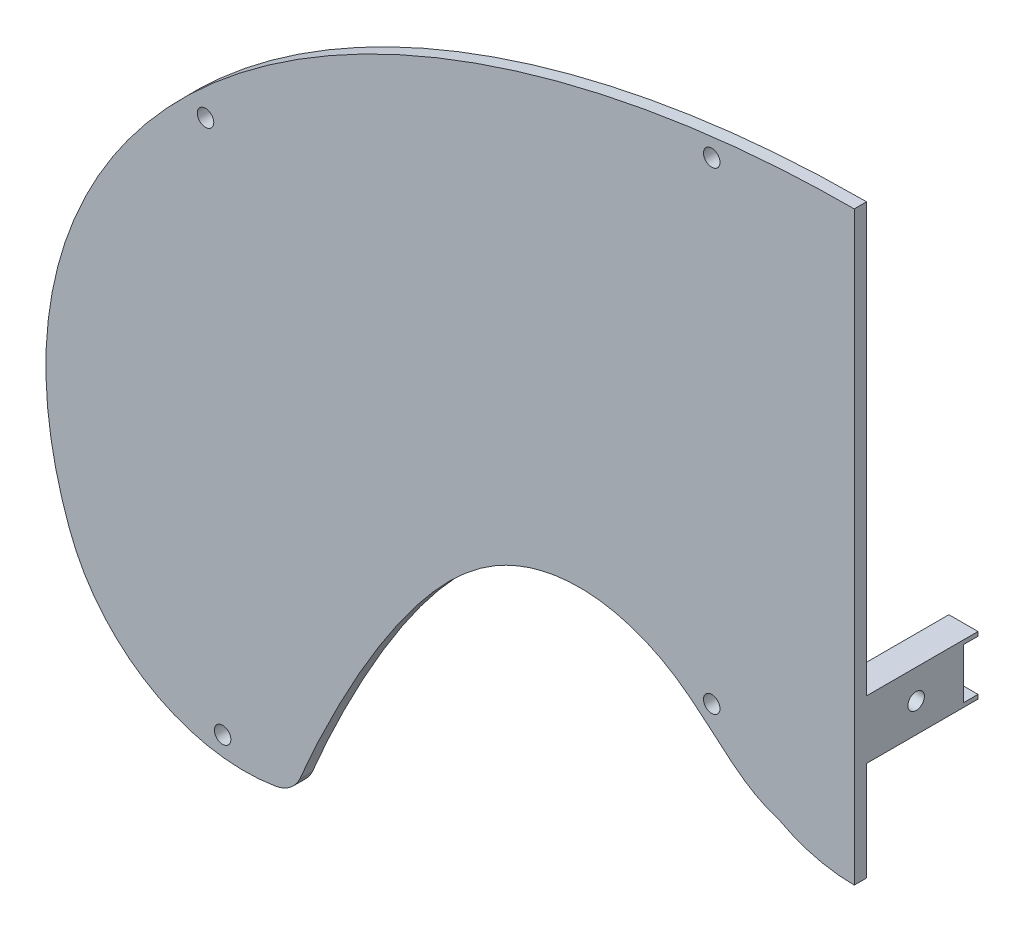
SolidWorks part; units mm, degrees
ref_plane "Alzado" through (0, 0, 0) normal (0, 0, 1) x (1, 0, 0)
ref_plane "Planta" through (0, 0, 0) normal (0, 1, 0) x (1, 0, 0)
ref_plane "Vista lateral" through (0, 0, 0) normal (1, 0, 0) x (0, 0, -1)
sketch "Croquis7" plane through (0, 0, 0) normal (0, 0, 1) x (-1, 0, 0)
  circle A31 centre (-153.1105, 56.1657) radius 2.25
  circle A33 centre (-34.5152, -9.6156) radius 2.25
  circle A35 centre (34.5978, -9.6156) radius 2
  arc A41 (140.3481, 60.5359) -> (134.4676, 56.1109) centre (141.679, 52.6474) ccw
  arc A42 (18.5035, 6.4502) -> (0.0413, 11.1657) centre (0.0413, -27.3343) ccw
  arc A43 (0.0413, 11.1657) -> (-18.4209, 6.4502) centre (0.0413, -27.3343) ccw
  arc A44 (190.316, 31.4795) -> (140.3481, 60.5359) centre (147.8664, 15.9723) ccw
  arc A45 (-134.385, 56.1109) -> (-140.2655, 60.5359) centre (-141.5964, 52.6474) ccw
  circle A47 centre (153.1931, 56.1657) radius 2
  circle A49 centre (-157.2515, -72.2296) radius 2.25
  circle A51 centre (-34.5152, -124.3045) radius 2.25
  circle A53 centre (34.5978, -124.3045) radius 2
  circle A55 centre (157.3341, -71.3124) radius 2
  spline S34 degree 3 poles (134.4676, 56.1109) (134.1497, 55.3341) (133.823, 54.562) (133.1625, 53.0214) (132.8278, 52.2534) (131.8131, 49.9551) (129.7405, 45.3812) (127.5541, 40.867) (124.537, 34.9015) (122.9771, 31.9456) (119.7406, 26.0953) (118.0639, 23.2008) (115.4414, 18.9154) (114.5493, 17.4963) (112.7238, 14.6799) (111.7904, 13.2827) (108.9309, 9.1433) (106.9422, 6.4488) (103.7895, 2.5408) (102.71, 1.2608) (101.0385, -0.6181) (100.4726, -1.2376) (99.3214, -2.461) (98.7352, -3.0657) (96.9496, -4.8484) (95.7253, -5.9925) (93.1935, -8.1717) (91.8856, -9.2063) (89.1637, -11.1369) (87.7504, -12.0335) (85.5424, -13.2632) (84.7899, -13.6545) (83.2733, -14.3869) (82.5072, -14.7293) (80.1852, -15.6842) (78.6055, -16.2244) (76.1869, -16.8847) (75.3725, -17.0799) (73.7268, -17.4186) (72.8936, -17.5624) (68.7052, -18.1459) (65.3663, -18.1723) (61.2066, -17.6857) (60.3753, -17.5622) (58.7142, -17.2624) (57.8851, -17.086) (55.4328, -16.486) (53.8333, -15.9902) (50.7014, -14.8176) (49.1688, -14.1408) (46.9194, -12.9918) (46.1761, -12.5854) (44.7184, -11.7347) (44.0033, -11.2901) (41.8979, -9.9002) (40.5487, -8.8972) (37.9154, -6.8) (36.6314, -5.7052) (34.0802, -3.4945) (32.813, -2.378) (30.2367, -0.2008) (28.9278, 0.8604) (26.2007, 2.837) (24.7825, 3.7527) (22.5133, 4.9374) (21.7312, 5.3009) (20.5388, 5.7796) (20.1373, 5.9286) (19.5289, 6.1355) (19.3251, 6.2018) (18.9151, 6.3283) (18.7092, 6.3889) (18.5035, 6.4502) knots 0 0 0 0 0.015625 0.015625 0.03125 0.03125 0.0625 0.125 0.125 0.1875 0.1875 0.25 0.25 0.28125 0.28125 0.3125 0.3125 0.375 0.375 0.40625 0.40625 0.421875 0.421875 0.4375 0.4375 0.46875 0.46875 0.5 0.5 0.53125 0.53125 0.546875 0.546875 0.5625 0.5625 0.59375 0.59375 0.609375 0.609375 0.625 0.625 0.6875 0.6875 0.703125 0.703125 0.71875 0.71875 0.75 0.75 0.78125 0.78125 0.796875 0.796875 0.8125 0.8125 0.84375 0.84375 0.875 0.875 0.90625 0.90625 0.9375 0.9375 0.96875 0.96875 0.984375 0.984375 0.992188 0.992188 0.996094 0.996094 1 1 1 1
  spline S35 degree 3 poles (0.0413, -130.8343) (6.1345, -130.8343) (18.2614, -130.4542) (30.2709, -129.3262) (42.2211, -127.8206) (48.1667, -126.8792) (59.9963, -124.6051) (65.8805, -123.2725) (74.6576, -120.9611) (79.034, -119.7273) (83.391, -118.3705) (86.2913, -117.4379) (87.7403, -116.9573) (94.9485, -114.4913) (100.6127, -112.3132) (111.7238, -107.5208) (117.1707, -104.9068) (127.8256, -99.1992) (133.0339, -96.1063) (139.3732, -91.8969) (140.6325, -91.0378) (143.1331, -89.2836) (144.3749, -88.388) (148.0522, -85.6602) (150.4464, -83.7821) (157.4477, -77.9604) (161.8749, -73.8302) (168.1008, -67.2053) (170.1073, -64.9256) (173.0021, -61.3872) (173.9479, -60.1879) (175.7992, -57.7476) (176.704, -56.5073) (181.0878, -50.2489) (184.1754, -45.0224) (188.0971, -36.8106) (189.2858, -34.0112) (190.6103, -30.4274) (190.8671, -29.7064) (191.3642, -28.2557) (191.6048, -27.5249) (192.2983, -25.3286) (192.7227, -23.8598) (194.6557, -16.493) (195.5989, -10.5266) (196.0792, -1.4638) (196.0831, 1.576) (195.8454, 6.1652) (195.725, 7.7032) (195.4053, 10.7544) (195.2061, 12.2713) (194.0174, 19.8128) (192.4537, 25.7099) (190.316, 31.4795) knots 0 0 0 0 0.0625 0.125 0.125 0.1875 0.1875 0.25 0.25 0.28125 0.296875 0.296875 0.3125 0.3125 0.375 0.375 0.4375 0.4375 0.5 0.5 0.515625 0.515625 0.53125 0.53125 0.5625 0.5625 0.625 0.625 0.65625 0.65625 0.671875 0.671875 0.6875 0.6875 0.75 0.75 0.78125 0.78125 0.789062 0.789062 0.796875 0.796875 0.8125 0.8125 0.875 0.875 0.90625 0.90625 0.921875 0.921875 0.9375 0.9375 1 1 1 1
  spline S36 degree 3 poles (-190.2396, 31.4627) (-192.3753, 25.6964) (-193.931, 19.8179) (-195.353, 10.8241) (-195.6746, 7.7968) (-195.9176, 3.2095) (-195.9586, 1.6681) (-195.9588, -1.3991) (-195.9184, -2.9265) (-195.5185, -10.5339) (-194.5674, -16.5243) (-192.6293, -23.8987) (-192.204, -25.3678) (-191.5098, -27.5631) (-191.2689, -28.2939) (-190.7708, -29.7454) (-190.5134, -30.4669) (-189.1858, -34.0543) (-187.9935, -36.8588) (-185.3684, -42.3469) (-183.9355, -45.0306) (-181.6166, -48.9709) (-180.8153, -50.2701) (-179.1576, -52.8408) (-178.2995, -54.1146) (-173.8945, -60.3876) (-170.029, -65.0712) (-161.7345, -73.886) (-157.3041, -78.0158) (-151.4553, -82.8734) (-150.2699, -83.8296) (-147.8686, -85.7121) (-146.6511, -86.6395) (-142.9656, -89.3694) (-140.4706, -91.1152) (-132.8814, -96.1488) (-127.6832, -99.2332) (-117.0444, -104.9282) (-111.6035, -107.5381) (-100.5002, -112.325) (-94.8377, -114.5017) (-87.6288, -116.9669) (-86.1801, -117.4472) (-83.2812, -118.3789) (-78.9261, -119.7345) (-74.5518, -120.9675) (-65.7783, -123.2771) (-59.8964, -124.6087) (-48.0711, -126.8813) (-42.1276, -127.8222) (-30.181, -129.3269) (-18.1749, -130.4544) (-6.0508, -130.8343) (0.0413, -130.8343) knots 0 0 0 0 0.0625 0.0625 0.09375 0.09375 0.109375 0.109375 0.125 0.125 0.1875 0.1875 0.203125 0.203125 0.210937 0.210937 0.21875 0.21875 0.25 0.25 0.28125 0.28125 0.296875 0.296875 0.3125 0.3125 0.375 0.375 0.4375 0.4375 0.453125 0.453125 0.46875 0.46875 0.5 0.5 0.5625 0.5625 0.625 0.625 0.6875 0.6875 0.703125 0.703125 0.71875 0.75 0.75 0.8125 0.8125 0.875 0.875 0.9375 1 1 1 1
  spline S37 degree 3 poles (-140.2655, 60.5359) (-142.8693, 60.9752) (-145.4727, 61.1815) (-149.3774, 61.1563) (-150.6788, 61.0918) (-152.6309, 60.9098) (-153.2815, 60.8349) (-154.5828, 60.6562) (-155.2349, 60.5521) (-158.4768, 59.9615) (-160.9933, 59.2705) (-164.6567, 57.918) (-165.8592, 57.4143) (-167.6345, 56.578) (-168.2215, 56.2858) (-169.3859, 55.674) (-169.9645, 55.3537) (-172.8074, 53.6975) (-174.9374, 52.1926) (-177.9226, 49.6738) (-178.8825, 48.7905) (-180.2687, 47.3985) (-180.7218, 46.9233) (-181.6098, 45.9503) (-182.0445, 45.4525) (-184.1498, 42.9327) (-185.6364, 40.7989) (-188.2287, 36.3043) (-189.3345, 33.9434) (-190.2396, 31.4627) knots 0 0 0 0 0.125 0.125 0.1875 0.1875 0.21875 0.21875 0.25 0.25 0.375 0.375 0.4375 0.4375 0.46875 0.46875 0.5 0.5 0.625 0.625 0.6875 0.6875 0.71875 0.71875 0.75 0.75 0.875 0.875 1 1 1 1
  spline S38 degree 3 poles (-18.4209, 6.4502) (-18.6239, 6.3897) (-18.8274, 6.3298) (-19.2315, 6.2052) (-19.4321, 6.1401) (-20.0298, 5.9374) (-20.4228, 5.7921) (-21.5864, 5.3276) (-23.8516, 4.2837) (-25.9572, 2.9439) (-27.9958, 1.4801) (-28.6649, 0.971) (-29.9839, -0.0733) (-31.9328, -1.678) (-33.8306, -3.3482) (-37.6482, -6.6606) (-40.2236, -8.8297) (-43.7321, -11.1693) (-44.4478, -11.6193) (-45.9083, -12.4816) (-46.6541, -12.8941) (-48.91, -14.0595) (-50.4472, -14.7456) (-53.5879, -15.9362) (-55.1916, -16.4402) (-57.65, -17.0517) (-58.4788, -17.2315) (-60.153, -17.5399) (-60.9902, -17.6671) (-65.1772, -18.1706) (-68.5295, -18.1508) (-72.7235, -17.5765) (-73.5654, -17.4332) (-75.2277, -17.0942) (-76.0496, -16.8986) (-78.4886, -16.2359) (-80.0788, -15.693) (-82.4131, -14.7345) (-83.1827, -14.391) (-84.705, -13.6564) (-85.4593, -13.2643) (-87.6863, -12.0236) (-89.1091, -11.119) (-91.846, -9.1738) (-93.1593, -8.1323) (-95.6997, -5.9411) (-96.9266, -4.7914) (-99.3113, -2.4055) (-100.4707, -1.1677) (-102.7053, 1.3503) (-103.7843, 2.6341) (-106.932, 6.544) (-108.9096, 9.2293) (-112.6931, 14.7116) (-114.4983, 17.5091) (-117.9753, 23.1911) (-119.6467, 26.0756) (-122.8791, 31.9168) (-124.4399, 34.8734) (-127.4635, 40.8505) (-128.9258, 43.8693) (-131.0393, 48.4296) (-132.0766, 50.7187) (-133.0806, 53.0229) (-133.7409, 54.5632) (-134.0674, 55.335) (-134.385, 56.1109) knots 0 0 0 0 0.003906 0.003906 0.007812 0.007812 0.015625 0.015625 0.03125 0.0625 0.0625 0.078125 0.078125 0.09375 0.125 0.125 0.1875 0.1875 0.203125 0.203125 0.21875 0.21875 0.25 0.25 0.28125 0.28125 0.296875 0.296875 0.3125 0.3125 0.375 0.375 0.390625 0.390625 0.40625 0.40625 0.4375 0.4375 0.453125 0.453125 0.46875 0.46875 0.5 0.5 0.53125 0.53125 0.5625 0.5625 0.59375 0.59375 0.625 0.625 0.6875 0.6875 0.75 0.75 0.8125 0.8125 0.875 0.875 0.9375 0.9375 0.96875 0.984375 0.984375 1 1 1 1
extrude "Saliente-Extruir5" add sketch "Croquis7" along normal blind 3
sketch "Croquis8" plane through (0, 0, 3) normal (0, 0, 1) x (1, 0, 0)
  line L0 (0, 0) -> (0, 20) construction
  line L2 (-7.1, 27.1) -> (7.1, 27.1)
  line L3 (-7.1, 27.1) -> (-7.1, 12.9)
  line L4 (-7.1, 12.9) -> (7.1, 12.9)
  line L5 (7.1, 27.1) -> (7.1, 12.9)
  line L6 (-7.1, 27.1) -> (7.1, 12.9) construction
  line L7 (-7.1, 12.9) -> (7.1, 27.1) construction
  dimension "D1" = 20
  dimension "D2" = 14.2
extrude "Saliente-Extruir6" add sketch "Croquis8" against normal blind 30
sketch "Croquis9" plane through (0, 0, -27) normal (0, 0, -1) x (-1, 0, 0)
  line L8 (-6.1, 26.1) -> (-6.1, 13.9)
  line L9 (-6.1, 13.9) -> (6.1, 13.9)
  line L10 (6.1, 13.9) -> (6.1, 26.1)
  line L11 (6.1, 26.1) -> (-6.1, 26.1)
  line L12 (-6.1, 26.1) -> (-6.1, 13.9)
  line L13 (-6.1, 13.9) -> (6.1, 13.9)
  line L14 (6.1, 13.9) -> (6.1, 26.1)
  line L15 (6.1, 26.1) -> (-6.1, 26.1)
  dimension "D1" = 1
extrude "Cortar-Extruir3" cut sketch "Croquis9" against normal blind 3.5
sketch "Croquis10" plane through (0, 0, 3) normal (0, 0, 1) x (1, 0, 0)
  line L0 (153.1105, 41.3343) -> (153.1105, -23.6657) construction
  line L2 (127.1105, 38.8343) -> (179.1105, 38.8343)
  line L3 (127.1105, 38.8343) -> (127.1105, -21.1657)
  line L4 (127.1105, -21.1657) -> (179.1105, -21.1657)
  line L5 (179.1105, 38.8343) -> (179.1105, -21.1657)
  line L6 (127.1105, 38.8343) -> (179.1105, -21.1657) construction
  line L7 (127.1105, -21.1657) -> (179.1105, 38.8343) construction
  circle A0 centre (153.1105, 41.3343) radius 1.5
  circle A1 centre (153.1105, -23.6657) radius 1.5
  point P2 (153.1105, 8.8343)
  point P9 (153.1105, -56.1657)
  dimension "D4" = 3
  dimension "D1" = 65
  dimension "D2" = 60
  dimension "D3" = 52
  dimension "D5" = 35
extrude "Cortar-Extruir4" cut sketch "Croquis10" against normal blind 10
sketch "Croquis11" plane through (-7.1, 0, 0) normal (-1, 0, 0) x (0, 0, 1)
  line L0 (0, 20) -> (-12, 20) construction
  line L1 (0, 27.1) -> (0, 12.9) construction
  circle A0 centre (-12, 20) radius 2
  dimension "D1" = 12
  dimension "D2" = 4
extrude "Cortar-Extruir5" cut sketch "Croquis11" against normal through all
sketch "Croquis12" plane through (0, 0, 3) normal (0, 0, 1) x (1, 0, 0)
  line L0 (-0.0413, -11.1657) -> (-0.0413, 130.8343)
  arc A0 (134.385, -56.1109) -> (140.2655, -60.5359) centre (141.5964, -52.6474) ccw construction
  arc A1 (134.385, -56.1109) -> (140.2655, -60.5359) centre (141.5964, -52.6474) ccw
  arc A2 (-18.5035, -6.4502) -> (18.4209, -6.4502) centre (-0.0413, 27.3343) ccw construction
  arc A3 (-0.0413, -11.1657) -> (18.4209, -6.4502) centre (-0.0413, 27.3343) ccw
  spline S0 degree 3 poles (-123.152, -1150.316) (-2465.4542, -298.4648) (133.6131, -401.2981) (195.353, -10.8241) (195.6746, -7.7968) (195.9176, -3.2095) (195.9586, -1.6681) (195.9588, 1.3991) (195.9184, 2.9265) (195.5185, 10.5339) (194.5674, 16.5243) (192.6293, 23.8987) (192.204, 25.3678) (191.5098, 27.5631) (191.2689, 28.2939) (190.7708, 29.7454) (190.5134, 30.4669) (189.1858, 34.0543) (187.9935, 36.8588) (185.3684, 42.3469) (183.9355, 45.0306) (181.6166, 48.9709) (180.8153, 50.2701) (179.1576, 52.8408) (178.2995, 54.1146) (173.8945, 60.3876) (170.029, 65.0712) (161.7345, 73.886) (157.3041, 78.0158) (151.4553, 82.8734) (150.2699, 83.8296) (147.8686, 85.7121) (146.6511, 86.6395) (142.9656, 89.3694) (140.4706, 91.1152) (132.8814, 96.1488) (127.6832, 99.2332) (117.0444, 104.9282) (111.6035, 107.5381) (100.5002, 112.325) (94.8377, 114.5017) (87.6288, 116.9669) (86.1801, 117.4472) (83.2812, 118.3789) (78.9261, 119.7345) (74.5518, 120.9675) (65.7783, 123.2771) (59.8964, 124.6087) (48.0711, 126.8813) (42.1276, 127.8222) (30.181, 129.3269) (-266.7613, 157.2118) (-635.885, -272.138) (-1122.8382, -1486.4707) knots -3.976508 -3.976508 -3.976508 -3.976508 0.0625 0.0625 0.09375 0.09375 0.109375 0.109375 0.125 0.125 0.1875 0.1875 0.203125 0.203125 0.210937 0.210937 0.21875 0.21875 0.25 0.25 0.28125 0.28125 0.296875 0.296875 0.3125 0.3125 0.375 0.375 0.4375 0.4375 0.453125 0.453125 0.46875 0.46875 0.5 0.5 0.5625 0.5625 0.625 0.625 0.6875 0.6875 0.703125 0.703125 0.71875 0.75 0.75 0.8125 0.8125 0.875 0.875 0.9375 3.966572 3.966572 3.966572 3.966572 only from (190.2396, -31.4627) to (-0.0413, 130.8343) construction
  spline S1 degree 3 poles (190.2396, -31.4627) (192.3753, -25.6964) (193.931, -19.8179) (195.353, -10.8241) (195.6746, -7.7968) (195.9176, -3.2095) (195.9586, -1.6681) (195.9588, 1.3991) (195.9184, 2.9265) (195.5185, 10.5339) (194.5674, 16.5243) (192.6293, 23.8987) (192.204, 25.3678) (191.5098, 27.5631) (191.2689, 28.2939) (190.7708, 29.7454) (190.5134, 30.4669) (189.1858, 34.0543) (187.9935, 36.8588) (185.3684, 42.3469) (183.9355, 45.0306) (181.6166, 48.9709) (180.8153, 50.2701) (179.1576, 52.8408) (178.2995, 54.1146) (173.8945, 60.3876) (170.029, 65.0712) (161.7345, 73.886) (157.3041, 78.0158) (151.4553, 82.8734) (150.2699, 83.8296) (147.8686, 85.7121) (146.6511, 86.6395) (142.9656, 89.3694) (140.4706, 91.1152) (132.8814, 96.1488) (127.6832, 99.2332) (117.0444, 104.9282) (111.6035, 107.5381) (100.5002, 112.325) (94.8377, 114.5017) (87.6288, 116.9669) (86.1801, 117.4472) (83.2812, 118.3789) (78.9261, 119.7345) (74.5518, 120.9675) (65.7783, 123.2771) (59.8964, 124.6087) (48.0711, 126.8813) (42.1276, 127.8222) (30.181, 129.3269) (18.1749, 130.4544) (6.0508, 130.8343) (-0.0413, 130.8343) knots 0 0 0 0 0.0625 0.0625 0.09375 0.09375 0.109375 0.109375 0.125 0.125 0.1875 0.1875 0.203125 0.203125 0.210937 0.210937 0.21875 0.21875 0.25 0.25 0.28125 0.28125 0.296875 0.296875 0.3125 0.3125 0.375 0.375 0.4375 0.4375 0.453125 0.453125 0.46875 0.46875 0.5 0.5 0.5625 0.5625 0.625 0.625 0.6875 0.6875 0.703125 0.703125 0.71875 0.75 0.75 0.8125 0.8125 0.875 0.875 0.9375 1 1 1 1
  spline S2 degree 3 poles (-187.5922, 1906.35) (-74.2976, 342.265) (37.2023, -61.8809) (149.3774, -61.1563) (150.6788, -61.0918) (152.6309, -60.9098) (153.2815, -60.8349) (154.5828, -60.6562) (155.2349, -60.5521) (158.4768, -59.9615) (160.9933, -59.2705) (164.6567, -57.918) (165.8592, -57.4143) (167.6345, -56.578) (168.2215, -56.2858) (169.3859, -55.674) (169.9645, -55.3537) (172.8074, -53.6975) (174.9374, -52.1926) (177.9226, -49.6738) (178.8825, -48.7905) (180.2687, -47.3985) (180.7218, -46.9233) (181.6098, -45.9503) (182.0445, -45.4525) (184.1498, -42.9327) (185.6364, -40.7989) (240.2569, 53.9039) (-28.6067, 338.5434) (-1341.2748, 1245.8082) knots -5.199154 -5.199154 -5.199154 -5.199154 0.125 0.125 0.1875 0.1875 0.21875 0.21875 0.25 0.25 0.375 0.375 0.4375 0.4375 0.46875 0.46875 0.5 0.5 0.625 0.625 0.6875 0.6875 0.71875 0.71875 0.75 0.75 0.875 0.875 6.017498 6.017498 6.017498 6.017498 only from (140.2655, -60.5359) to (190.2396, -31.4627) construction
  spline S3 degree 3 poles (140.2655, -60.5359) (142.8693, -60.9752) (145.4727, -61.1815) (149.3774, -61.1563) (150.6788, -61.0918) (152.6309, -60.9098) (153.2815, -60.8349) (154.5828, -60.6562) (155.2349, -60.5521) (158.4768, -59.9615) (160.9933, -59.2705) (164.6567, -57.918) (165.8592, -57.4143) (167.6345, -56.578) (168.2215, -56.2858) (169.3859, -55.674) (169.9645, -55.3537) (172.8074, -53.6975) (174.9374, -52.1926) (177.9226, -49.6738) (178.8825, -48.7905) (180.2687, -47.3985) (180.7218, -46.9233) (181.6098, -45.9503) (182.0445, -45.4525) (184.1498, -42.9327) (185.6364, -40.7989) (188.2287, -36.3043) (189.3345, -33.9434) (190.2396, -31.4627) knots 0 0 0 0 0.125 0.125 0.1875 0.1875 0.21875 0.21875 0.25 0.25 0.375 0.375 0.4375 0.4375 0.46875 0.46875 0.5 0.5 0.625 0.625 0.6875 0.6875 0.71875 0.71875 0.75 0.75 0.875 0.875 1 1 1 1
  spline S4 degree 3 poles (922.8054, -1790.0041) (-23.5741, 0.3542) (2.2971, -11.4265) (19.2315, -6.2052) (19.4321, -6.1401) (20.0298, -5.9374) (20.4228, -5.7921) (21.5864, -5.3276) (23.8516, -4.2837) (25.9572, -2.9439) (27.9958, -1.4801) (28.6649, -0.971) (29.9839, 0.0733) (31.9328, 1.678) (33.8306, 3.3482) (37.6482, 6.6606) (40.2236, 8.8297) (43.7321, 11.1693) (44.4478, 11.6193) (45.9083, 12.4816) (46.6541, 12.8941) (48.91, 14.0595) (50.4472, 14.7456) (53.5879, 15.9362) (55.1916, 16.4402) (57.65, 17.0517) (58.4788, 17.2315) (60.153, 17.5399) (60.9902, 17.6671) (65.1772, 18.1706) (68.5295, 18.1508) (72.7235, 17.5765) (73.5654, 17.4332) (75.2277, 17.0942) (76.0496, 16.8986) (78.4886, 16.2359) (80.0788, 15.693) (82.4131, 14.7345) (83.1827, 14.391) (84.705, 13.6564) (85.4593, 13.2643) (87.6863, 12.0236) (89.1091, 11.119) (91.846, 9.1738) (93.1593, 8.1323) (95.6997, 5.9411) (96.9266, 4.7914) (99.3113, 2.4055) (100.4707, 1.1677) (102.7053, -1.3503) (103.7843, -2.6341) (106.932, -6.544) (108.9096, -9.2293) (112.6931, -14.7116) (114.4983, -17.5091) (117.9753, -23.1911) (119.6467, -26.0756) (122.8791, -31.9168) (124.4399, -34.8734) (127.4635, -40.8505) (128.9258, -43.8693) (131.0393, -48.4296) (132.0766, -50.7187) (133.0806, -53.0229) (156.2675, -107.1059) (161.6077, -168.4196) (-1604.5833, -1038.8984) knots -0.319529 -0.319529 -0.319529 -0.319529 0.003906 0.003906 0.007812 0.007812 0.015625 0.015625 0.03125 0.0625 0.0625 0.078125 0.078125 0.09375 0.125 0.125 0.1875 0.1875 0.203125 0.203125 0.21875 0.21875 0.25 0.25 0.28125 0.28125 0.296875 0.296875 0.3125 0.3125 0.375 0.375 0.390625 0.390625 0.40625 0.40625 0.4375 0.4375 0.453125 0.453125 0.46875 0.46875 0.5 0.5 0.53125 0.53125 0.5625 0.5625 0.59375 0.59375 0.625 0.625 0.6875 0.6875 0.75 0.75 0.8125 0.8125 0.875 0.875 0.9375 0.9375 0.96875 0.984375 0.984375 2.066024 2.066024 2.066024 2.066024 only from (18.4209, -6.4502) to (134.385, -56.1109) construction
  spline S5 degree 3 poles (18.4209, -6.4502) (18.6239, -6.3897) (18.8274, -6.3298) (19.2315, -6.2052) (19.4321, -6.1401) (20.0298, -5.9374) (20.4228, -5.7921) (21.5864, -5.3276) (23.8516, -4.2837) (25.9572, -2.9439) (27.9958, -1.4801) (28.6649, -0.971) (29.9839, 0.0733) (31.9328, 1.678) (33.8306, 3.3482) (37.6482, 6.6606) (40.2236, 8.8297) (43.7321, 11.1693) (44.4478, 11.6193) (45.9083, 12.4816) (46.6541, 12.8941) (48.91, 14.0595) (50.4472, 14.7456) (53.5879, 15.9362) (55.1916, 16.4402) (57.65, 17.0517) (58.4788, 17.2315) (60.153, 17.5399) (60.9902, 17.6671) (65.1772, 18.1706) (68.5295, 18.1508) (72.7235, 17.5765) (73.5654, 17.4332) (75.2277, 17.0942) (76.0496, 16.8986) (78.4886, 16.2359) (80.0788, 15.693) (82.4131, 14.7345) (83.1827, 14.391) (84.705, 13.6564) (85.4593, 13.2643) (87.6863, 12.0236) (89.1091, 11.119) (91.846, 9.1738) (93.1593, 8.1323) (95.6997, 5.9411) (96.9266, 4.7914) (99.3113, 2.4055) (100.4707, 1.1677) (102.7053, -1.3503) (103.7843, -2.6341) (106.932, -6.544) (108.9096, -9.2293) (112.6931, -14.7116) (114.4983, -17.5091) (117.9753, -23.1911) (119.6467, -26.0756) (122.8791, -31.9168) (124.4399, -34.8734) (127.4635, -40.8505) (128.9258, -43.8693) (131.0393, -48.4296) (132.0766, -50.7187) (133.0806, -53.0229) (133.7409, -54.5632) (134.0674, -55.335) (134.385, -56.1109) knots 0 0 0 0 0.003906 0.003906 0.007812 0.007812 0.015625 0.015625 0.03125 0.0625 0.0625 0.078125 0.078125 0.09375 0.125 0.125 0.1875 0.1875 0.203125 0.203125 0.21875 0.21875 0.25 0.25 0.28125 0.28125 0.296875 0.296875 0.3125 0.3125 0.375 0.375 0.390625 0.390625 0.40625 0.40625 0.4375 0.4375 0.453125 0.453125 0.46875 0.46875 0.5 0.5 0.53125 0.53125 0.5625 0.5625 0.59375 0.59375 0.625 0.625 0.6875 0.6875 0.75 0.75 0.8125 0.8125 0.875 0.875 0.9375 0.9375 0.96875 0.984375 0.984375 1 1 1 1
extrude "Cortar-Extruir6" cut sketch "Croquis12" against normal blind 30 and the other way blind 10
